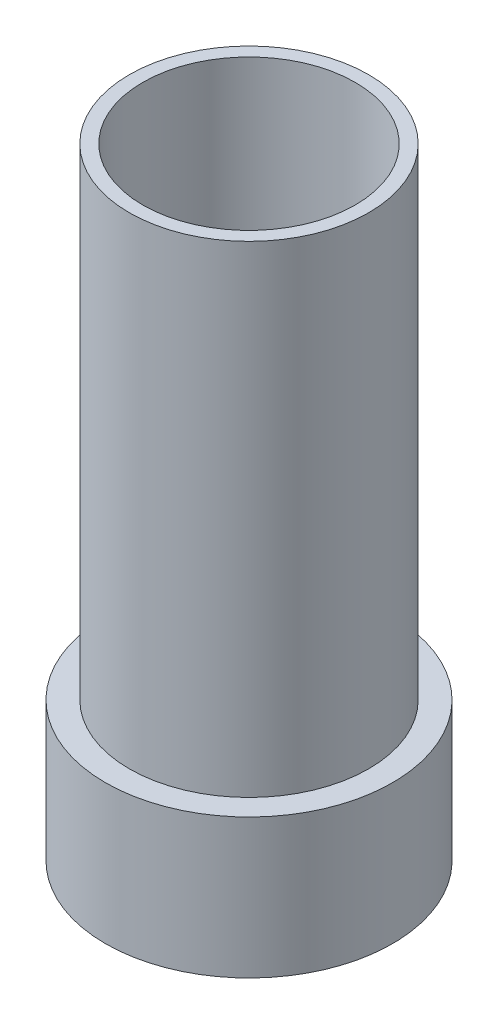
SolidWorks part; units mm, degrees
material "AISI 1020"
ref_plane "Front Plane" through (0, 0, 0) normal (0, 0, 1) x (1, 0, 0)
ref_plane "Top Plane" through (0, 0, 0) normal (0, 1, 0) x (1, 0, 0)
ref_plane "Right Plane" through (0, 0, 0) normal (1, 0, 0) x (0, 0, -1)
sketch "Sketch1" plane through (0, 0, 0) normal (0, 1, 0) x (1, 0, 0)
  circle A0 centre (13.6327, 6.0794) radius 7.0485
  circle A1 centre (13.6327, 6.0794) radius 7.9375
  dimension "D1" = 14.097
  dimension "D2" = 15.875
extrude "Boss-Extrude1" add sketch "Sketch1" along normal blind 41.2
sketch "Sketch2" plane through (0, 0, 0) normal (0, -1, 0) x (1, 0, 0)
  circle A0 centre (13.6327, -6.0794) radius 7.9375
  circle A1 centre (13.6327, -6.0794) radius 9.525
  dimension "D1" = 19.05
extrude "Boss-Extrude2" add sketch "Sketch2" against normal blind 9.25
